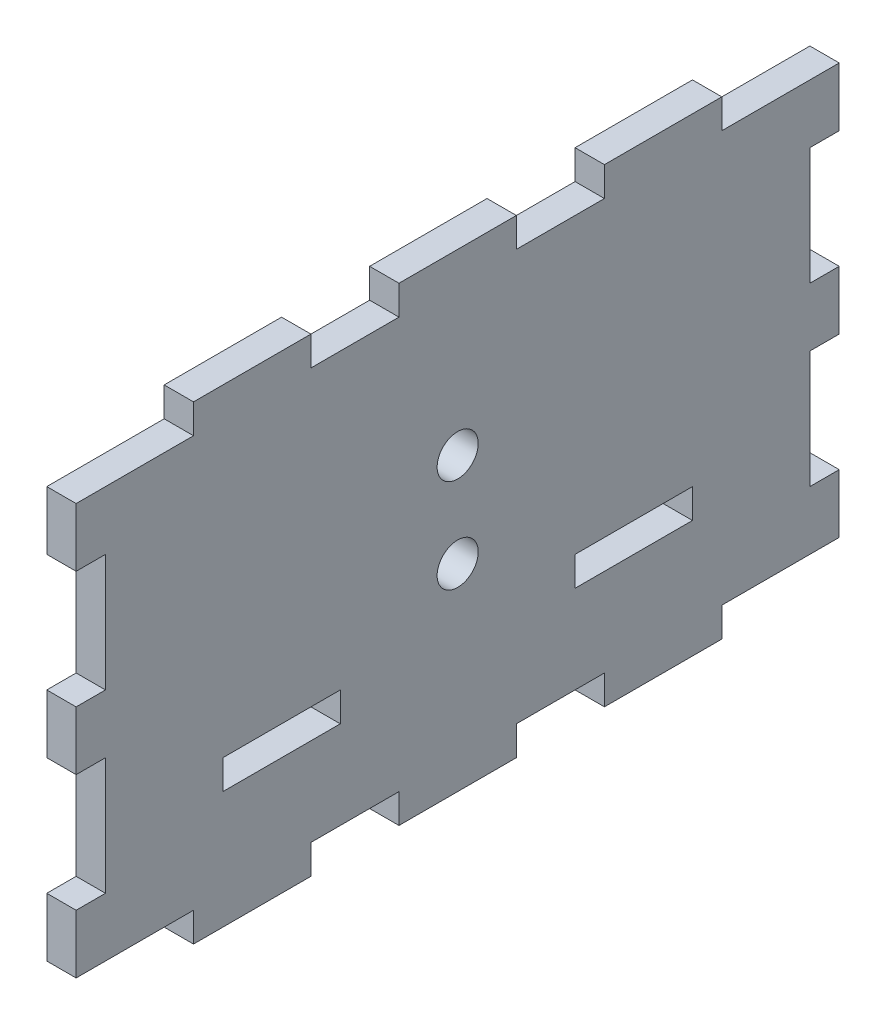
SolidWorks part; units mm, degrees
ref_plane "Front Plane" through (0, 0, 0) normal (0, 0, 1) x (1, 0, 0)
ref_plane "Top Plane" through (0, 0, 0) normal (0, 1, 0) x (1, 0, 0)
ref_plane "Right Plane" through (0, 0, 0) normal (1, 0, 0) x (0, 0, -1)
sketch "Sketch1" plane through (0, 0, 0) normal (1, 0, 0) x (0, 0, -1)
  line L0 (-109.8871, 0) -> (84.0492, 0) construction
  line L1 (0, 64.1388) -> (0, -100.6158) construction
  line L2 (-60, 35) -> (-45, 35)
  line L3 (-60, 35) -> (60, 35) construction
  line L4 (-60, 35) -> (-60, -35) construction
  line L5 (-60, -35) -> (60, -35) construction
  line L6 (60, 35) -> (60, -35) construction
  line L7 (-60, 35) -> (60, -35) construction
  line L8 (-60, -35) -> (60, 35) construction
  line L9 (-45, 35) -> (-45, 40)
  line L10 (-45, 40) -> (-25, 40)
  line L11 (-25, 40) -> (-25, 35)
  line L12 (-10, 35) -> (-10, 40)
  line L13 (-10, 40) -> (10, 40)
  line L14 (10, 40) -> (10, 35)
  line L15 (-25, 35) -> (-10, 35)
  line L16 (25, 35) -> (25, 40)
  line L17 (25, 40) -> (45, 40)
  line L18 (45, 40) -> (45, 35)
  line L19 (10, 35) -> (25, 35)
  line L20 (45, -35) -> (60, -35)
  line L21 (10, -35) -> (25, -35)
  line L22 (45, -40) -> (45, -35)
  line L23 (45, 35) -> (60, 35)
  line L24 (60, 40) -> (80, 40) [skipped]
  line L25 (80, 40) -> (80, 35) [skipped]
  line L26 (60, 35) -> (60, 40) [skipped]
  line L27 (25, -40) -> (45, -40)
  line L28 (25, -35) -> (25, -40)
  line L29 (-25, -35) -> (-10, -35)
  line L30 (10, -40) -> (10, -35)
  line L31 (-10, -40) -> (10, -40)
  line L32 (-10, -35) -> (-10, -40)
  line L33 (-25, -40) -> (-25, -35)
  line L34 (-45, -40) -> (-25, -40)
  line L35 (-45, -35) -> (-45, -40)
  line L36 (-60, -35) -> (-45, -35)
  line L37 (-60, 35) -> (-65, 35)
  line L38 (-65, 35) -> (-65, 25)
  line L39 (-65, 25) -> (-60, 25)
  line L40 (-60, 25) -> (-60, 5)
  line L41 (-60, 5) -> (-65, 5)
  line L42 (-65, 5) -> (-65, -5)
  line L43 (-65, -5) -> (-60, -5)
  line L44 (-60, -5) -> (-60, -25)
  line L45 (-60, -25) -> (-65, -25)
  line L46 (-65, -25) -> (-65, -35)
  line L47 (-65, -35) -> (-60, -35)
  line L48 (65, -35) -> (60, -35)
  line L49 (60, 35) -> (65, 35)
  line L50 (65, -25) -> (65, -35)
  line L51 (60, -25) -> (65, -25)
  line L52 (60, -5) -> (60, -25)
  line L53 (65, -5) -> (60, -5)
  line L54 (65, 5) -> (65, -5)
  line L55 (60, 5) -> (65, 5)
  line L56 (60, 25) -> (60, 5)
  line L57 (65, 25) -> (60, 25)
  line L58 (65, 35) -> (65, 25)
  point P5 (0, 0)
  dimension "D1" = 70
  dimension "D2" = 120
  dimension "D3" = 4
extrude "Boss-Extrude1" add sketch "Sketch1" along normal blind 5 contours L58 L49 L23 L18 L17 L16 L19 L14 L13 L12 L15 L11 L10 L9 L2 L37 L38 L39 L40 L41 L42 L43 L44 L45 L46 L47 L36 L35 L34 L33 L29 L32 L31 L30 L21 L28 L27 L22 L20 L48 L50 L51 L52 L53 L54 L55 L56 L57
sketch "Sketch2" plane through (0, 0, 0) normal (1, 0, 0) x (0, 0, -1)
  line L0 (0, 1.6234) -> (39.3291, 1.6234) construction
  line L7 (0, 1.6234) -> (-48.4922, 1.6234) construction
  line L8 (0, 17.5211) -> (0, -27.1046) construction
  circle A0 centre (0, 9.6234) radius 3.5
  circle A1 centre (0, -6.3766) radius 3.5
  dimension "D1" = 7
  dimension "D2" = 8
sketch "Sketch3" plane through (5, 0, 0) normal (1, 0, 0) x (0, 0, -1)
  line L0 (-60, -5) -> (-60, -25) construction
  line L1 (-60, -20) -> (60, -20) construction
  line L2 (60, -5) -> (60, -25) construction
  line L3 (-25, -35) -> (-10, -35) construction
  line L4 (0, -3.8143) -> (0, -32.5252) construction
  line L5 (20, -20) -> (20, -15)
  line L6 (20, -15) -> (40, -15)
  line L7 (40, -15) -> (40, -20)
  line L8 (40, -20) -> (20, -20)
  line L9 (-40, -20) -> (-20, -20)
  line L10 (-40, -15) -> (-40, -20)
  line L11 (-20, -15) -> (-40, -15)
  line L12 (-20, -20) -> (-20, -15)
  dimension "D1" = 120
  dimension "D2" = 15
  dimension "D3" = 5
  dimension "D4" = 20
  dimension "D5" = 20
extrude "Cut-Extrude2" cut sketch "Sketch3" against normal up to surface (5 mm away) up to face at (0, 0, 0)
extrude "Cut-Extrude3" cut sketch "Sketch2" along normal up to surface (5 mm away) up to face at (5, -17.5, 30)
